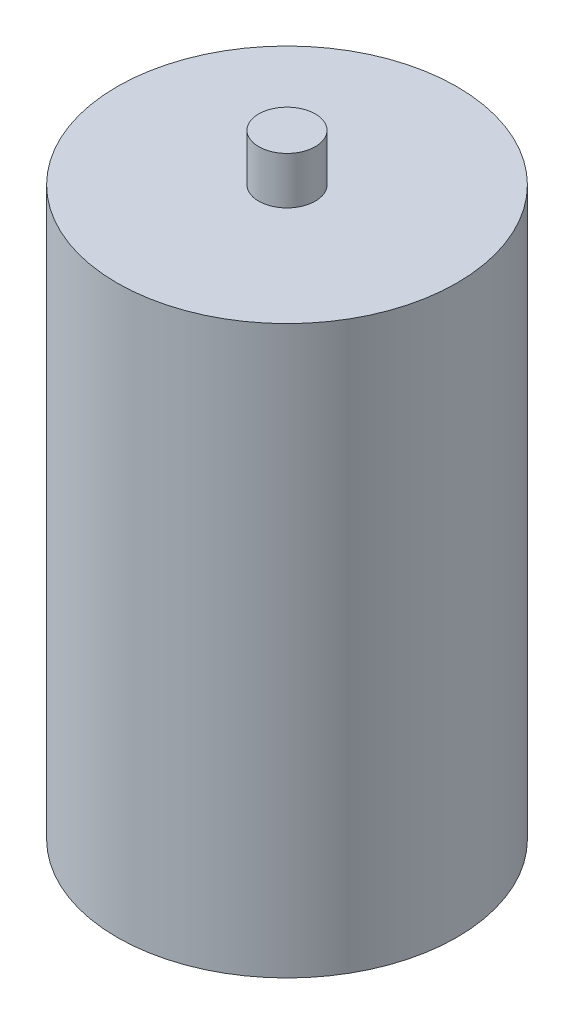
SolidWorks part; units mm, degrees
ref_plane "Front" through (0, 0, 0) normal (0, 0, 1) x (1, 0, 0)
ref_plane "Top" through (0, 0, 0) normal (0, 1, 0) x (1, 0, 0)
ref_plane "Right" through (0, 0, 0) normal (1, 0, 0) x (0, 0, -1)
sketch "Esquisse2" plane through (0, 0, 0) normal (0, 0, 1) x (1, 0, 0)
  line L0 (0, 0) -> (3, 0)
  line L1 (3, 0) -> (3, 5)
  line L2 (3, 5) -> (18, 5)
  line L3 (18, 5) -> (18, 65)
  line L4 (18, 65) -> (3, 65)
  line L5 (3, 65) -> (3, 70)
  line L6 (3, 70) -> (0, 70)
  line L7 (0, 70) -> (0, 0)
  point P6 (3.5213, 60)
  dimension "D1" = 3
  dimension "D2" = 18
  dimension "D3" = 5
  dimension "D4" = 5
  dimension "D5" = 60
revolve "Révolution1" add sketch "Esquisse2" angle 360 about L7
